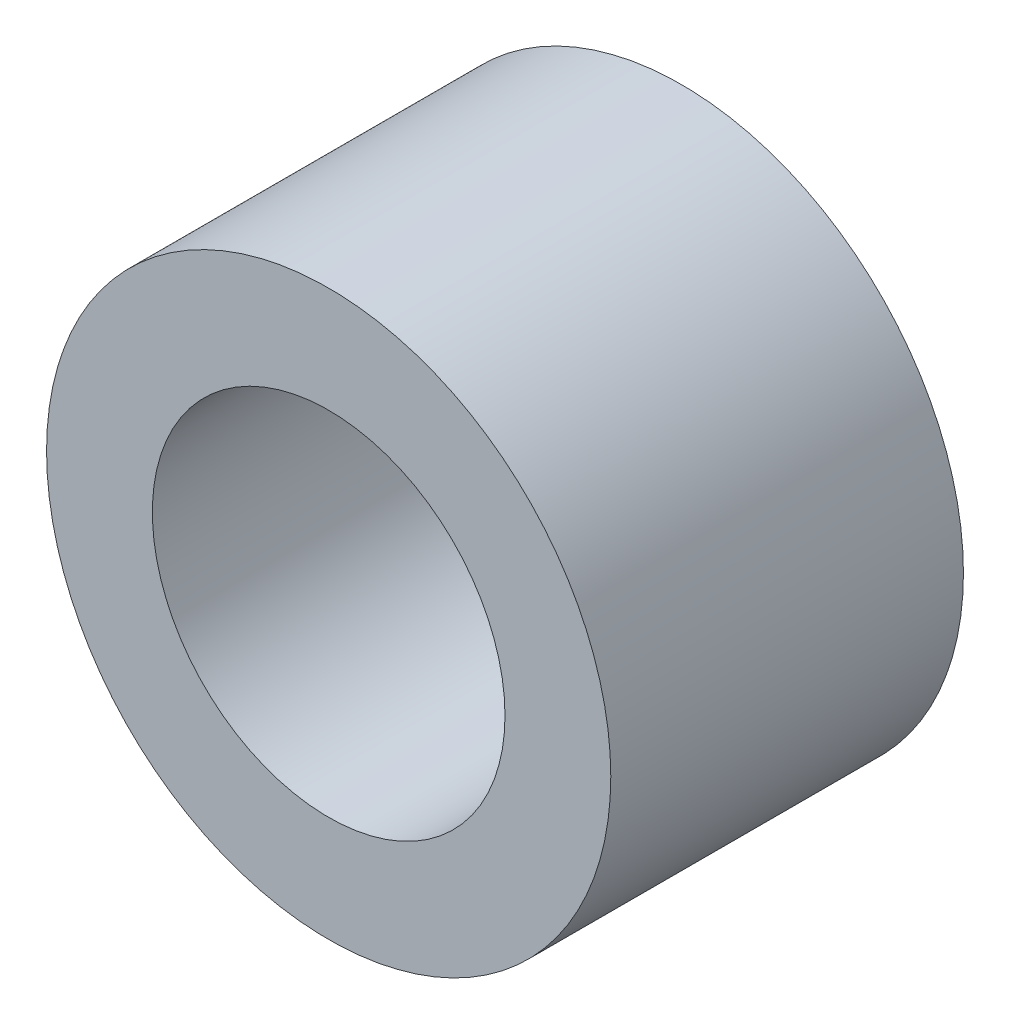
SolidWorks part; units mm, degrees
ref_plane "Front Plane" through (0, 0, 0) normal (0, 0, 1) x (1, 0, 0)
ref_plane "Top Plane" through (0, 0, 0) normal (0, 1, 0) x (1, 0, 0)
ref_plane "Right Plane" through (0, 0, 0) normal (1, 0, 0) x (0, 0, -1)
sketch "Sketch1" plane through (0, 0, 0) normal (0, 0, 1) x (1, 0, 0)
  circle A0 centre (0, 0) radius 7.9375
  circle A1 centre (0, 0) radius 12.7
  dimension "D1" = 15.875
  dimension "D2" = 25.4
extrude "Boss-Extrude1" add sketch "Sketch1" along normal mid plane 15.875
